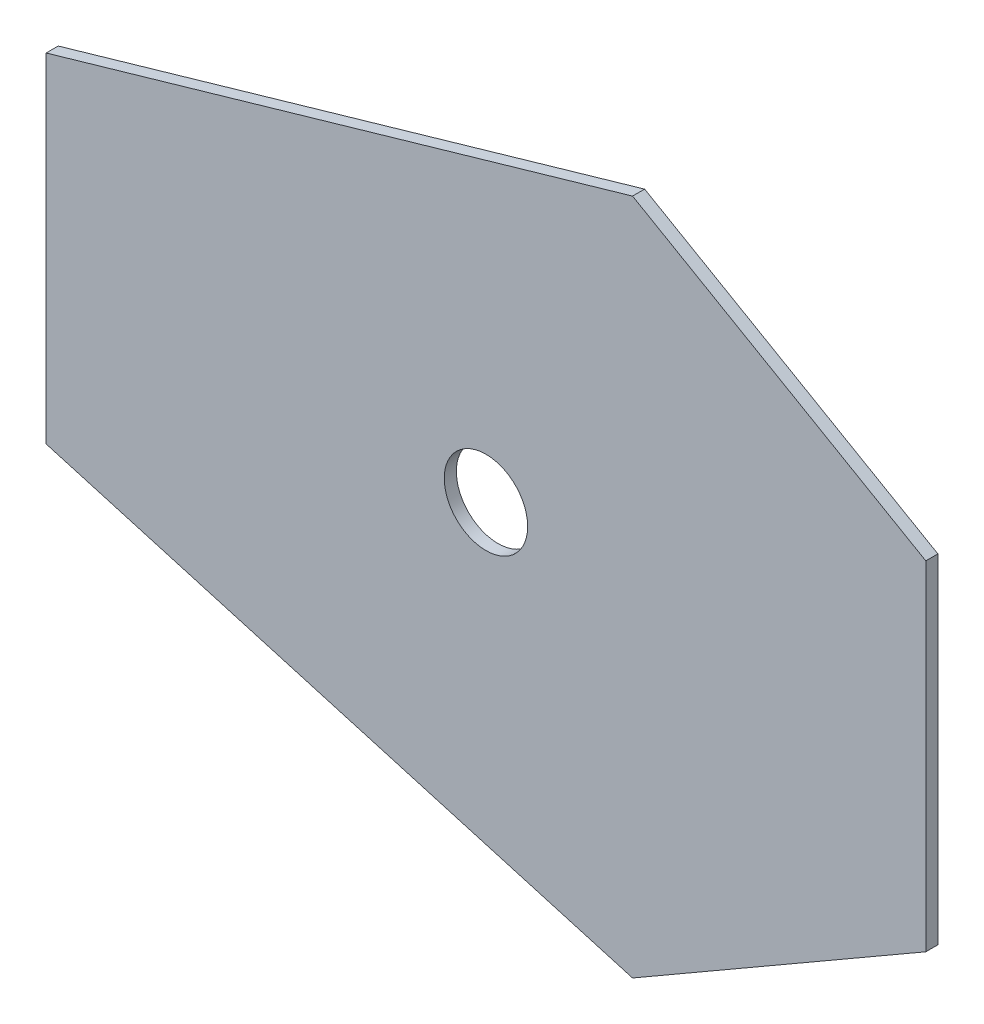
SolidWorks part; units mm, degrees
ref_plane "Front Plane" through (0, 0, 0) normal (0, 0, 1) x (1, 0, 0)
ref_plane "Top Plane" through (0, 0, 0) normal (0, 1, 0) x (1, 0, 0)
ref_plane "Right Plane" through (0, 0, 0) normal (1, 0, 0) x (0, 0, -1)
sketch "Sketch1" plane through (0, 0, 0) normal (0, 0, 1) x (1, 0, 0)
  line L6 (-41.5231, -14) -> (6.9744, -28)
  line L7 (6.9744, -28) -> (31.2231, -14)
  line L8 (31.2231, -14) -> (31.2231, 14)
  line L9 (31.2231, 14) -> (6.9744, 28)
  line L10 (6.9744, 28) -> (-41.5231, 14)
  line L11 (-41.5231, 14) -> (-41.5231, -14)
  line L12 (-41.5231, -14) -> (6.9744, -28)
  line L13 (6.9744, -28) -> (31.2231, -14)
  line L14 (31.2231, -14) -> (31.2231, 14)
  line L15 (31.2231, 14) -> (6.9744, 28)
  line L16 (6.9744, 28) -> (-41.5231, 14)
  line L17 (-41.5231, 14) -> (-41.5231, -14)
  circle A0 centre (-5.15, 0) radius 3.45 construction
  circle A1 centre (-5.15, 0) radius 3.45
  dimension "D1" = 0
extrude "Boss-Extrude1" add sketch "Sketch1" along normal blind 1
